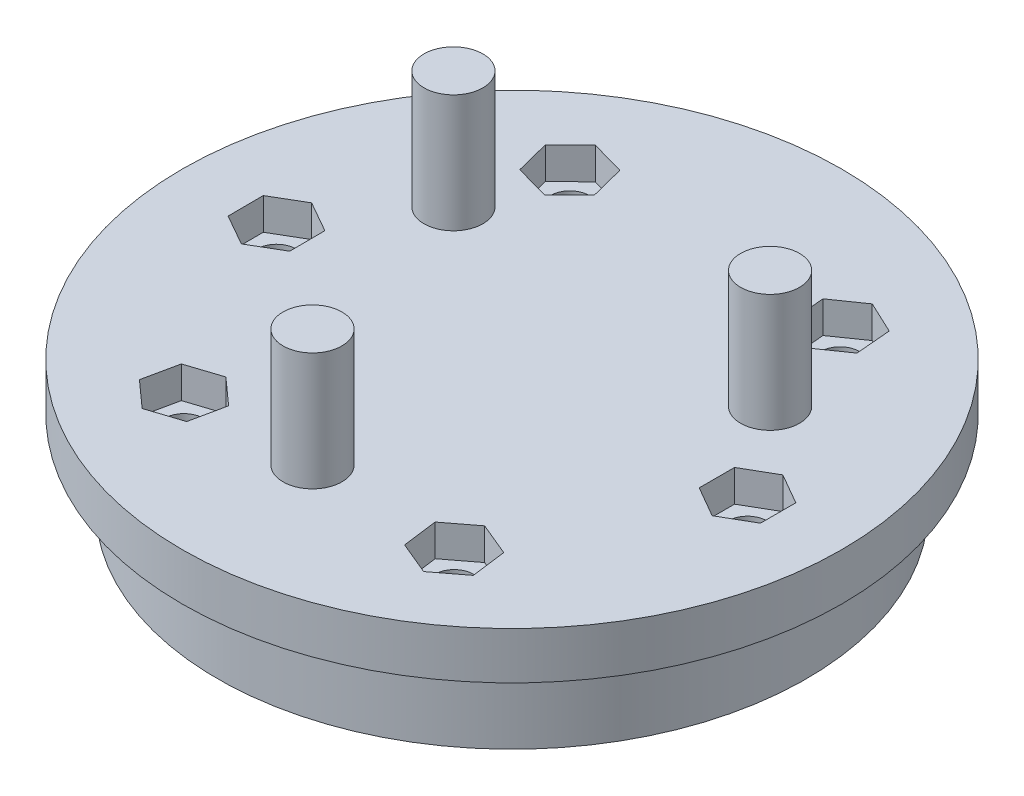
SolidWorks part; units mm, degrees
ref_plane "Front Plane" through (0, 0, 0) normal (0, 0, 1) x (1, 0, 0)
ref_plane "Top Plane" through (0, 0, 0) normal (0, 1, 0) x (1, 0, 0)
ref_plane "Right Plane" through (0, 0, 0) normal (1, 0, 0) x (0, 0, -1)
sketch "Sketch3" plane through (0, 0, 0) normal (0, 1, 0) x (1, 0, 0)
  circle A0 centre (0, 0) radius 28
  dimension "D1" = 56
extrude "Boss-Extrude1" add sketch "Sketch3" along normal blind 4
sketch "Sketch6" plane through (0, 0, 0) normal (0, -1, 0) x (1, 0, 0)
  circle A0 centre (0, 0) radius 25
  dimension "D1" = 50
extrude "Boss-Extrude4" add sketch "Sketch6" along normal blind 7
sketch "Sketch7" plane through (0, 4, 0) normal (0, 1, 0) x (1, 0, 0)
  line L0 (0, 0) -> (28, 0) construction
  line L1 (0, 0) -> (-19.1581, 12.205) construction
  line L2 (0, 0) -> (-0.884, -20.2476) construction
  line L3 (0, 0) -> (24.8363, 12.929) construction
  circle A0 centre (0, 0) radius 28 construction
  circle A5 centre (14.4139, 7.5034) radius 2.5
  circle A6 centre (-13.7051, 8.7311) radius 2.5
  circle A7 centre (-0.7088, -16.2345) radius 2.5
  dimension "D7" = 27.5
  dimension "D2" = 120
  dimension "D1" = 120
extrude "Boss-Extrude5" add sketch "Sketch7" along normal blind 10
sketch "Sketch8" plane through (0, 0, 0) normal (0, -1, 0) x (1, 0, 0)
  line L0 (0, 0) -> (20, 0) construction
  line L1 (0, 25) -> (0, -25) construction
  line L2 (0, 0) -> (11.4715, 16.383) construction
  line L3 (0, 0) -> (11.4715, -16.383) construction
  line L4 (0, 0) -> (-13.6508, -19.4954) construction
  line L5 (0, 0) -> (-20, 0) construction
  line L6 (0, 0) -> (-11.4715, -16.383) construction
  line L7 (0, 0) -> (-11.4715, 16.383) construction
  circle A0 centre (20, 0) radius 1.65
  circle A1 centre (0, 0) radius 25 construction
  circle A2 centre (0, 0) radius 25 construction
  circle A3 centre (-20, 0) radius 1.65
  circle A4 centre (11.4715, 16.383) radius 1.65
  circle A5 centre (-11.4715, -16.383) radius 1.65
  circle A6 centre (11.4715, -16.383) radius 1.65
  circle A7 centre (-11.4715, 16.383) radius 1.65
  dimension "D1" = 55
  dimension "D2" = 55
  dimension "D3" = 35
  dimension "D4" = 55
  dimension "D5" = 35
extrude "Cut-Extrude1" cut sketch "Sketch8" against normal through all and the other way blind 10
sketch "Sketch11" plane through (0, 4, 0) normal (0, 1, 0) x (1, 0, 0)
  line L1 (11.8581, -19.3603) -> (14.2432, -17.5369)
  line L2 (14.2432, -17.5369) -> (13.8566, -14.5597)
  line L3 (13.8566, -14.5597) -> (11.085, -13.4058)
  line L4 (11.085, -13.4058) -> (8.6999, -15.2292)
  line L5 (8.6999, -15.2292) -> (9.0865, -18.2064)
  line L6 (9.0865, -18.2064) -> (11.8581, -19.3603)
  line L7 (-12.0914, -19.3206) -> (-9.2375, -18.3886)
  line L8 (-9.2375, -18.3886) -> (-8.6176, -15.4511)
  line L9 (-8.6176, -15.4511) -> (-10.8516, -13.4455)
  line L10 (-10.8516, -13.4455) -> (-13.7056, -14.3774)
  line L11 (-13.7056, -14.3774) -> (-14.3254, -17.315)
  line L12 (-14.3254, -17.315) -> (-12.0914, -19.3206)
  line L13 (-22.5906, -1.5173) -> (-19.9813, -3.0022)
  line L14 (-19.9813, -3.0022) -> (-17.3907, -1.4849)
  line L15 (-17.3907, -1.4849) -> (-17.4094, 1.5173)
  line L16 (-17.4094, 1.5173) -> (-20.0187, 3.0022)
  line L17 (-20.0187, 3.0022) -> (-22.6093, 1.4849)
  line L18 (-22.6093, 1.4849) -> (-22.5906, -1.5173)
  line L19 (20, -3.0022) -> (22.6, -1.5011)
  line L20 (22.6, -1.5011) -> (22.6, 1.5011)
  line L21 (22.6, 1.5011) -> (20, 3.0022)
  line L22 (20, 3.0022) -> (17.4, 1.5011)
  line L23 (17.4, 1.5011) -> (17.4, -1.5011)
  line L24 (17.4, -1.5011) -> (20, -3.0022)
  line L25 (9.0083, 14.6668) -> (11.7262, 13.3916)
  line L26 (11.7262, 13.3916) -> (14.1895, 15.1079)
  line L27 (14.1895, 15.1079) -> (13.9348, 18.0993)
  line L28 (13.9348, 18.0993) -> (11.2168, 19.3744)
  line L29 (11.2168, 19.3744) -> (8.7536, 17.6582)
  line L30 (8.7536, 17.6582) -> (9.0083, 14.6668)
  line L31 (-10.7297, 13.4739) -> (-8.5812, 15.5709)
  line L32 (-8.5812, 15.5709) -> (-9.3231, 18.48)
  line L33 (-9.3231, 18.48) -> (-12.2134, 19.2922)
  line L34 (-12.2134, 19.2922) -> (-14.3618, 17.1952)
  line L35 (-14.3618, 17.1952) -> (-13.62, 14.286)
  line L36 (-13.62, 14.286) -> (-10.7297, 13.4739)
  circle A0 centre (11.4715, -16.383) radius 2.6 construction
  circle A1 centre (-11.4715, -16.383) radius 2.6 construction
  circle A2 centre (-20, 0) radius 2.6 construction
  circle A3 centre (20, 0) radius 2.6 construction
  circle A4 centre (11.4715, 16.383) radius 2.6 construction
  circle A5 centre (-11.4715, 16.383) radius 2.6 construction
  dimension "D1" = 5.2
extrude "Cut-Extrude3" cut sketch "Sketch11" against normal blind 2.7
